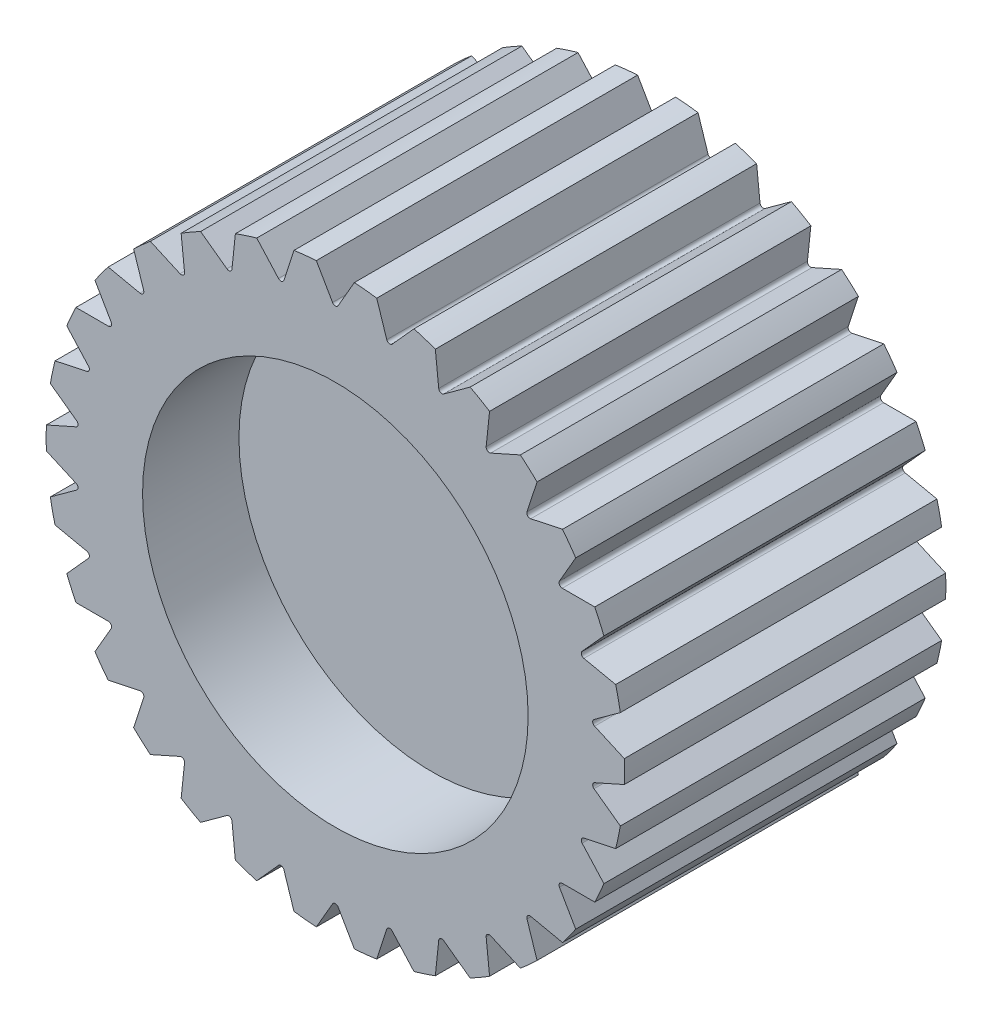
SolidWorks part; units mm, degrees
ref_plane "Front Plane" through (0, 0, 0) normal (0, 0, 1) x (1, 0, 0)
ref_plane "Top Plane" through (0, 0, 0) normal (0, 1, 0) x (1, 0, 0)
ref_plane "Right Plane" through (0, 0, 0) normal (1, 0, 0) x (0, 0, -1)
sketch "Sketch1" plane through (0, 0, 0) normal (0, 0, 1) x (1, 0, 0)
  circle A0 centre (0, 0) radius 9
  dimension "D1" = 18
extrude "Boss-Extrude1" add sketch "Sketch1" along normal blind 10
sketch "Sketch2" plane through (0, 0, 10) normal (0, 0, 1) x (1, 0, 0)
  circle A0 centre (0, 0) radius 6
  dimension "D1" = 12
extrude "Cut-Extrude1" cut sketch "Sketch2" against normal blind 3
sketch "Sketch3" plane through (0, 0, 10) normal (0, 0, 1) x (1, 0, 0)
  line L0 (-0.6, 8.9941) -> (0.6, 8.9941) construction
  line L1 (-1.6333, 10.7854) -> (1.6333, 10.7854)
  line L2 (5.5, 0) -> (-5.5, 0) construction
  line L3 (0, -5.5) -> (0, 5.5) construction
  line L4 (0, 8.9941) -> (0, 7.954) construction
  line L5 (0.0866, 8.1041) -> (0.6, 8.9941)
  line L6 (0.6, 8.9941) -> (1.6333, 10.7854)
  line L7 (-0.0866, 8.1041) -> (-0.6, 8.9941)
  line L8 (-0.6, 8.9941) -> (-1.6333, 10.7854)
  circle A0 centre (0, 0) radius 6 construction
  arc A1 (0.0866, 8.1041) -> (-0.0866, 8.1041) centre (0, 8.1541) cw
  point P3 (0, 8.9941)
  dimension "D2" = 0.1
  dimension "D1" = 1.2
  dimension "D3" = 0.84
  dimension "D4" = 2.6314
  dimension "D5" = 8.1041
extrude "Cut-Extrude2" cut sketch "Sketch3" against normal through all
pattern_circular "CirPattern1" count 30 over 360 about axis through (0, 0, 0) along (0, 0, 1) of "Cut-Extrude2"
